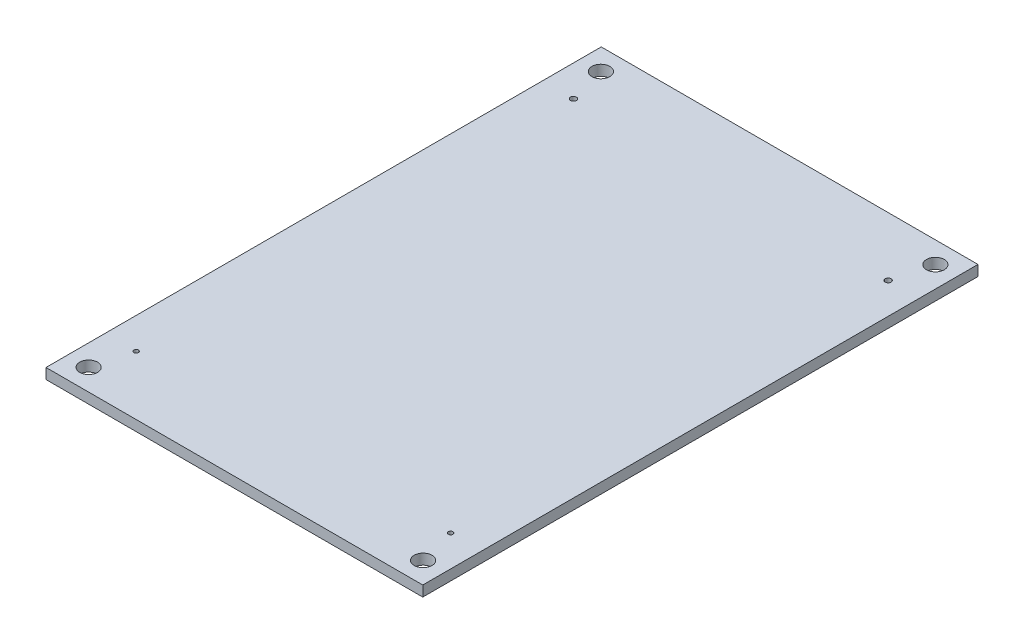
SolidWorks part; units mm, degrees
ref_plane "Front Plane" through (0, 0, 0) normal (0, 0, 1) x (1, 0, 0)
ref_plane "Top Plane" through (0, 0, 0) normal (0, 1, 0) x (1, 0, 0)
ref_plane "Right Plane" through (0, 0, 0) normal (1, 0, 0) x (0, 0, -1)
sketch "Sketch1" plane through (0, 0, 0) normal (0, 1, 0) x (1, 0, 0)
  line L0 (0, 0) -> (-28.5, 0) construction
  line L1 (-28.5, 42) -> (28.5, 42)
  line L2 (-28.5, 42) -> (-28.5, -42)
  line L3 (-28.5, -42) -> (28.5, -42)
  line L4 (28.5, 42) -> (28.5, -42)
  line L6 (0, 42) -> (0, 0) construction
  circle A0 centre (-25.3, 38.75) radius 1.35
  circle A1 centre (-25.3, -38.75) radius 1.35
  circle A2 centre (25.3, -38.75) radius 1.35
  circle A3 centre (25.3, 38.75) radius 1.35
  circle A4 centre (-23.8, 33.1) radius 0.45
  circle A5 centre (-23.8, -33.07) radius 0.35
  circle A6 centre (23.8, -33.07) radius 0.35
  circle A7 centre (23.8, 33.1) radius 0.45
  dimension "D3" = 2.7
  dimension "D4" = 77.5
  dimension "D6" = 0.9
  dimension "D8" = 5.65
  dimension "D10" = 0.7
  dimension "D1" = 84
  dimension "D2" = 57
  dimension "D5" = 50.6
  dimension "D7" = 66.17
  dimension "D9" = 47.6
sketch "Sketch2" plane through (0, 0, 0) normal (0, 1, 0) x (1, 0, 0)
  line L4 (28.5, 42) -> (-28.5, 42)
  line L5 (28.5, -42) -> (28.5, 42)
  line L6 (-28.5, -42) -> (28.5, -42)
  line L7 (-28.5, 42) -> (-28.5, -42)
  line L8 (28.5, 42) -> (-28.5, 42)
  line L9 (28.5, -42) -> (28.5, 42)
  line L10 (-28.5, -42) -> (28.5, -42)
  line L11 (-28.5, 42) -> (-28.5, -42)
  circle A0 centre (23.8, -33.07) radius 0.35 construction
  circle A1 centre (25.3, 38.75) radius 1.35
  circle A2 centre (25.3, 38.75) radius 1.35
  circle A3 centre (25.3, -38.75) radius 1.35
  circle A4 centre (25.3, -38.75) radius 1.35
  circle A5 centre (-25.3, -38.75) radius 1.35
  circle A6 centre (-25.3, -38.75) radius 1.35
  circle A7 centre (-25.3, 38.75) radius 1.35
  circle A8 centre (-25.3, 38.75) radius 1.35
  circle A9 centre (-23.8, -33.07) radius 0.35 construction
  circle A10 centre (23.8, 33.1) radius 0.45 construction
  circle A11 centre (-23.8, 33.1) radius 0.45 construction
  circle A12 centre (23.8, -33.07) radius 0.35
  circle A13 centre (-23.8, -33.07) radius 0.35
  circle A14 centre (23.8, 33.1) radius 0.45
  circle A15 centre (-23.8, 33.1) radius 0.45
  dimension "D1" = 0
  dimension "D2" = 0
  dimension "D3" = 0
  dimension "D4" = 0
  dimension "D5" = 0
extrude "Extrude1" add sketch "Sketch2" along normal mid plane 1.5875
